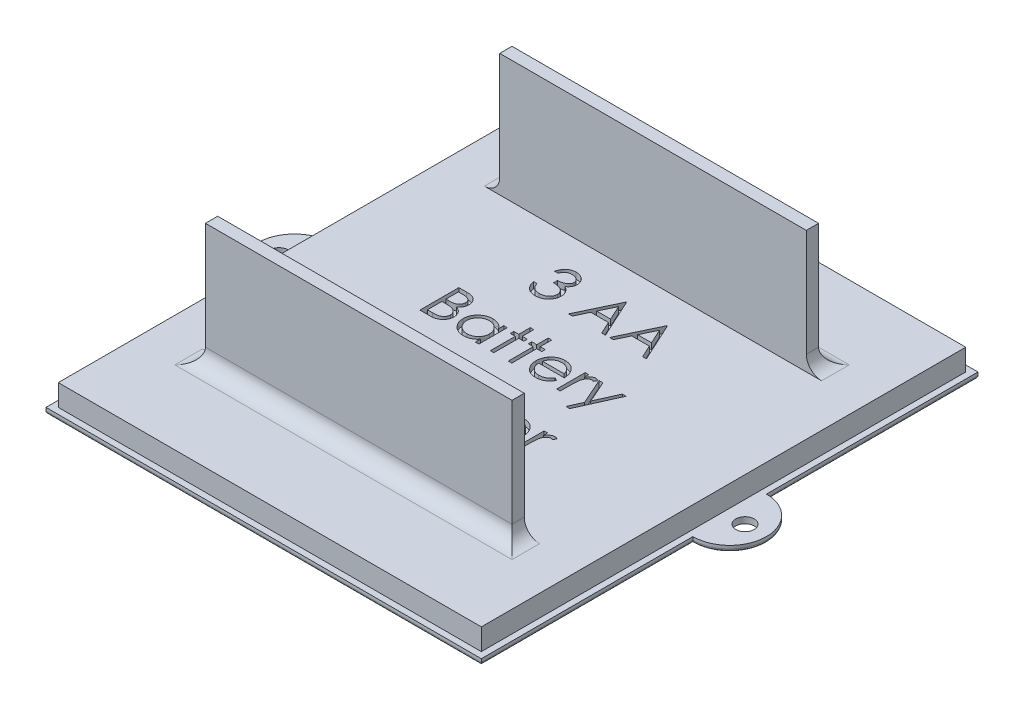
SolidWorks part; units mm, degrees
other "Markup1"
sketch "Sketch11" plane through (-41.5, 7, -35.5) normal (0, 1, 0) x (1, 0, 0)
sketch "Sketch12" plane through (-41.5, 7, -35.5) normal (0, 1, 0) x (1, 0, 0)
sketch "Sketch13" plane through (-41.5, 7, -35.5) normal (0, 1, 0) x (1, 0, 0)
sketch "Sketch15" plane through (-41.5, 7, -35.5) normal (0, 1, 0) x (1, 0, 0)
sketch "Sketch16" plane through (-41.5, 7, -35.5) normal (0, 1, 0) x (1, 0, 0)
sketch "Sketch17" plane through (-41.5, 7, -35.5) normal (0, 1, 0) x (1, 0, 0)
sketch "Sketch18" plane through (-41.5, 7, -35.5) normal (0, 1, 0) x (1, 0, 0)
sketch "Sketch19" plane through (-41.5, 7, -35.5) normal (0, 1, 0) x (1, 0, 0)
sketch "Sketch20" plane through (-41.5, 12, -35.5) normal (0, 1, 0) x (1, 0, 0)
sketch "Sketch21" plane through (-41.5, 12, -35.5) normal (0, 1, 0) x (1, 0, 0)
sketch "Sketch22" plane through (-41.5, 12, -35.5) normal (0, 1, 0) x (1, 0, 0)
sketch "Sketch31" plane through (-41.5, 25.5, -40.5) normal (0, 1, 0) x (1, 0, 0)
sketch "Sketch32" plane through (-41.5, 25.5, -40.5) normal (0, 1, 0) x (1, 0, 0)
sketch "Sketch38" plane through (-41.5, 25.5, -40.5) normal (0, 1, 0) x (1, 0, 0)
sketch "Sketch39" plane through (-41.5, 25.5, -40.5) normal (0, 1, 0) x (1, 0, 0)
sketch "Sketch40" plane through (-41.5, 25.5, -40.5) normal (0, 1, 0) x (1, 0, 0)
sketch "Sketch41" plane through (-41.5, 24.5, -40.5) normal (0, 1, 0) x (1, 0, 0)
sketch "Sketch48" plane through (-41.5, 24.5, -40.5) normal (0, 1, 0) x (1, 0, 0)
sketch "Sketch49" plane through (-41.5, 24.5, -40.5) normal (0, 1, 0) x (1, 0, 0)
sketch "Sketch50" plane through (-41.5, 24.5, -40.5) normal (0, 1, 0) x (1, 0, 0)
ref_plane "Front Plane" through (0, 0, 0) normal (0, 0, 1) x (1, 0, 0)
ref_plane "Top Plane" through (0, 0, 0) normal (0, 1, 0) x (1, 0, 0)
ref_plane "Right Plane" through (0, 0, 0) normal (1, 0, 0) x (0, 0, -1)
sketch "Sketch1" plane through (0, 0, 0) normal (0, 1, 0) x (1, 0, 0)
  line L1 (-35.5, -40.5) -> (35.5, -40.5)
  line L2 (-35.5, -40.5) -> (-35.5, 40.5)
  line L3 (-35.5, 40.5) -> (35.5, 40.5)
  line L4 (35.5, -40.5) -> (35.5, 40.5)
  line L5 (-35.5, -40.5) -> (35.5, 40.5) construction
  line L6 (-35.5, 40.5) -> (35.5, -40.5) construction
  point P0 (0, 0)
  dimension "D1" = 81
  dimension "D2" = 71
extrude "Boss-Extrude1" add sketch "Sketch1" along normal blind 4.5
sketch "text" plane through (0, 4.5, 0) normal (0, 1, 0) x (1, 0, 0)
  line L0 (-35.4043, 11.8177) -> (35.5957, 11.8177) construction
  text T0 "3 AA\r\nBattery \r\nHolder" font "Century Gothic" height in points 24
extrude "Cut-Extrude1" cut sketch "text" against normal blind 1
sketch "Sketch4" plane through (0, 4.5, 0) normal (0, 1, 0) x (1, 0, 0)
  line L0 (-35.5, 40.5) -> (-35.5, -40.5) construction
  line L1 (-35.5, 6) -> (-35.5, -6)
  arc A0 (-35.5, 6) -> (-35.5, -6) centre (-35.5, 0) ccw
  dimension "D1" = 6
extrude "Boss-Extrude3" add sketch "Sketch4" against normal up to surface (4.5 mm away) up to face at (0, 0, 0)
sketch "Sketch5" plane through (0, 4.5, 0) normal (0, 1, 0) x (1, 0, 0)
  line L0 (-35.5, 40.5) -> (-35.5, 6) construction
  circle A0 centre (-38, 0) radius 1.5
  dimension "D1" = 3
  dimension "D2" = 2.5
extrude "Cut-Extrude2" cut sketch "Sketch5" against normal up to surface (4.5 mm away) up to face at (-12.8333, 0, 0)
mirror "Mirror3" about plane through (0, 0, 0) normal (1, 0, 0) of "Boss-Extrude3", "Cut-Extrude2"
sketch "Sketch9" plane through (0, 4.5, 0) normal (0, 1, 0) x (1, 0, 0)
  line L0 (35.5, 40.5) -> (-35.5, 40.5) construction
  line L1 (-25, 25) -> (25, 25)
  line L2 (-25, 25) -> (-25, 23)
  line L3 (-25, 23) -> (25, 23)
  line L4 (25, 25) -> (25, 23)
  line L5 (-13.475, 0) -> (13.475, 0) construction
  point P5 (0, 25)
  point P8 (0, 40.5)
  dimension "D1" = 50
  dimension "D2" = 2
  dimension "D3" = 23
extrude "top track" add sketch "Sketch9" along normal blind 20 contours L2 L1 L4 L3
sketch "Sketch51" plane through (0, 4.5, 0) normal (0, 1, 0) x (1, 0, 0)
  line L0 (-35.5, 40.5) -> (-35.5, 6) construction
  line L1 (34.5, 39.5) -> (-34.5, 39.5)
  line L2 (34.5, 39.5) -> (34.5, -39.5)
  line L3 (34.5, -39.5) -> (-34.5, -39.5)
  line L4 (-34.5, 39.5) -> (-34.5, -39.5)
  line L5 (34.5, 39.5) -> (-34.5, -39.5) construction
  line L6 (34.5, -39.5) -> (-34.5, 39.5) construction
  line L7 (35.5, 40.5) -> (-35.5, 40.5) construction
  line L8 (-44.5, 49.5) -> (-44.5, -49.5)
  line L9 (44.5, -49.5) -> (-44.5, -49.5)
  line L10 (44.5, 49.5) -> (44.5, -49.5)
  line L11 (44.5, 49.5) -> (-44.5, 49.5)
  point P0 (0, 0)
  dimension "D1" = 1
  dimension "D2" = 1
  dimension "D3" = 10
extrude "Cut-Extrude25" cut sketch "Sketch51" against normal blind 3.5
fillet "Fillet2" radius 0.5 8 edges at (-35.5, 0, -23.25) (-41.5, 0, 0) (-35.5, 0, 23.25) (0, 0, 40.5) (35.5, 0, 23.25) (41.5, 0, 0) (35.5, 0, -23.25) (0, 0, -40.5)
fillet "Fillet3" radius 2.5 3 edges at (25, 4.5, -24) (0, 4.5, -25) (-25, 4.5, -24)
mirror "Mirror4" about plane through (0, 0, 0) normal (0, 0, 1) of "Fillet3", "top track"
equation "\"Screw_Diameter\"=3"
